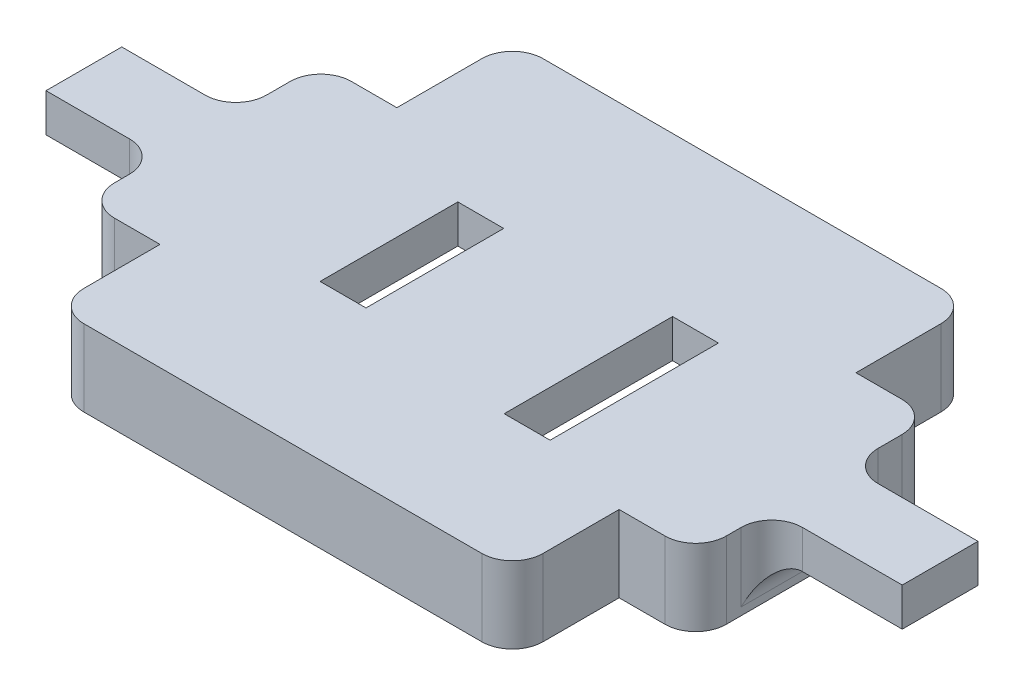
SolidWorks part; units mm, degrees
ref_plane "Front Plane" through (0, 0, 0) normal (0, 0, 1) x (1, 0, 0)
ref_plane "Top Plane" through (0, 0, 0) normal (0, 1, 0) x (1, 0, 0)
ref_plane "Right Plane" through (0, 0, 0) normal (1, 0, 0) x (0, 0, -1)
sketch "Sketch1" plane through (0, 0, 0) normal (0, 1, 0) x (1, 0, 0)
  line L0 (51.2258, 192.0334) -> (107.1758, 192.0334)
  line L1 (51.2258, 192.0334) -> (51.2258, 196.9834)
  line L2 (107.1758, 192.0334) -> (107.1758, 196.9834)
  line L3 (51.2258, 196.9834) -> (107.1758, 196.9834)
  line L4 (51.2258, 192.0334) -> (107.1758, 196.9834) construction
  line L5 (107.1758, 192.0334) -> (51.2258, 196.9834) construction
  point P1 (79.2008, 194.5084)
extrude "Boss-Extrude1" add sketch "Sketch1" along normal blind 2.5
sketch "Sketch2" plane through (0, 0, 0) normal (0, 1, 0) x (1, 0, 0)
  line L0 (63.6508, 180.0848) -> (93.6508, 180.0848)
  line L5 (63.6508, 180.0848) -> (63.6508, 210.0848)
  line L6 (93.6508, 180.0848) -> (93.6508, 210.0848)
  line L7 (63.6508, 210.0848) -> (93.6508, 210.0848)
  line L8 (63.6508, 180.0848) -> (93.6508, 210.0848) construction
  line L9 (93.6508, 180.0848) -> (63.6508, 210.0848) construction
extrude "Boss-Extrude2" add sketch "Sketch2" along normal blind 2.5
sketch "Sketch3" plane through (0, 0, 0) normal (0, -1, 0) x (1, 0, 0)
  line L5 (63.6508, -210.0848) -> (93.6508, -210.0848)
  line L11 (63.6508, -210.0848) -> (63.6508, -180.0848)
  line L12 (63.6508, -180.0848) -> (93.6508, -180.0848)
  line L14 (93.6508, -210.0848) -> (93.6508, -180.0848)
  line L15 (67.6258, -205.8334) -> (90.7758, -205.8334)
  line L16 (67.6258, -205.8334) -> (67.6258, -183.1834)
  line L17 (67.6258, -183.1834) -> (90.7758, -183.1834)
  line L18 (90.7758, -205.8334) -> (90.7758, -183.1834)
  line L19 (67.6258, -205.8334) -> (90.7758, -183.1834) construction
  line L20 (67.6258, -183.1834) -> (90.7758, -205.8334) construction
  point P4 (79.2008, -194.5084)
extrude "Boss-Extrude3" add sketch "Sketch3" along normal blind 2.5
sketch "Sketch4" plane through (0, 0, 0) normal (0, -1, 0) x (1, 0, 0)
  line L1 (70.9758, -190.1934) -> (73.9758, -190.1934)
  line L2 (70.9758, -190.1934) -> (70.9758, -199.1934)
  line L3 (70.9758, -199.1934) -> (73.9758, -199.1934)
  line L4 (73.9758, -190.1934) -> (73.9758, -199.1934)
  line L5 (70.9758, -190.1934) -> (73.9758, -199.1934) construction
  line L6 (70.9758, -199.1934) -> (73.9758, -190.1934) construction
  point P0 (72.4758, -194.6934)
extrude "Cut-Extrude1" cut sketch "Sketch4" against normal through all
fillet "Fillet1" radius 2 4 edges at (63.6508, 0, -210.0848) (93.6508, 0, -210.0848) (93.6508, 0, -180.0848) (63.6508, 0, -180.0848)
sketch "Sketch5" plane through (0, 2.5, 0) normal (0, 1, 0) x (1, 0, 0)
  line L0 (63.6508, 187.0591) -> (58.6798, 187.0591)
  line L1 (63.6508, 192.0334) -> (63.6508, 182.0848) construction
  line L2 (58.6798, 187.0591) -> (58.6798, 202.5341)
  line L3 (63.6508, 202.5341) -> (58.6798, 202.5341)
  line L4 (63.6508, 208.0848) -> (63.6508, 196.9834) construction
  line L5 (63.6508, 187.0591) -> (63.6508, 202.5341)
  line L8 (93.6508, 187.0591) -> (98.6508, 187.0591)
  line L9 (93.6508, 182.0848) -> (93.6508, 192.0334) construction
  line L10 (93.6508, 196.9834) -> (93.6508, 208.0848) construction
  line L11 (93.6508, 202.5341) -> (98.6508, 202.5341)
  line L12 (93.6508, 202.5341) -> (93.6508, 187.0591)
  line L13 (98.6508, 187.0591) -> (98.6508, 202.5341)
extrude "Boss-Extrude4" add sketch "Sketch5" against normal blind 5
fillet "Fillet2" radius 2 10 edges at (58.6798, 1.25, -196.9834) (58.6798, 1.25, -192.0334) (58.6798, 0, -194.5084) (98.6508, 1.25, -192.0334) (98.6508, 0, -194.5084) (98.6508, 1.25, -196.9834) (98.6508, 0, -187.0591) (98.6508, 0, -202.5341) (58.6798, 0, -202.5341) (58.6798, 0, -187.0591)
sketch "Sketch6" plane through (0, 0, 0) normal (0, -1, 0) x (1, 0, 0)
  line L0 (85.9758, -198.0334) -> (85.9758, -190.4134) construction
  line L2 (87.4758, -188.7234) -> (84.4758, -188.7234)
  line L3 (87.4758, -188.7234) -> (87.4758, -199.7234)
  line L4 (87.4758, -199.7234) -> (84.4758, -199.7234)
  line L5 (84.4758, -188.7234) -> (84.4758, -199.7234)
  line L6 (87.4758, -188.7234) -> (84.4758, -199.7234) construction
  line L7 (87.4758, -199.7234) -> (84.4758, -188.7234) construction
  point P4 (85.9758, -194.2234)
extrude "Cut-Extrude2" cut sketch "Sketch6" against normal through all
